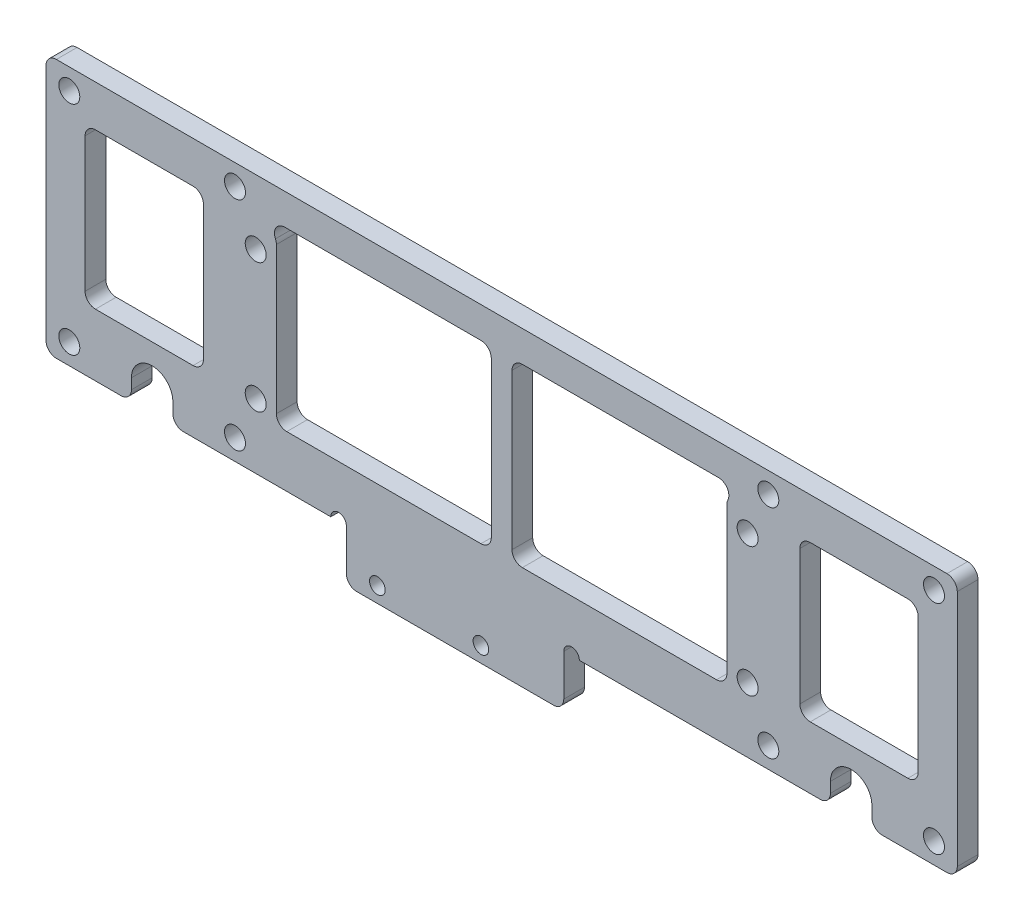
SolidWorks part; units mm, degrees
material "Thornel Mat VMA"
ref_plane "前视基准面" through (0, 0, 0) normal (0, 0, 1) x (1, 0, 0)
ref_plane "上视基准面" through (0, 0, 0) normal (0, 1, 0) x (1, 0, 0)
ref_plane "右视基准面" through (0, 0, 0) normal (1, 0, 0) x (0, 0, -1)
other "Configuration Table"
sketch "草图1" plane through (0, 0, 0) normal (0, 0, 1) x (1, 0, 0)
  line L1 (-88, -25) -> (88, -25)
  line L2 (-88, -25) -> (-88, 25)
  line L3 (-88, 25) -> (88, 25)
  line L4 (88, -25) -> (88, 25)
  line L5 (-88, -25) -> (88, 25) construction
  line L6 (-88, 25) -> (88, -25) construction
  point P0 (0, 0)
  dimension "D1" = 176
  dimension "D2" = 50
extrude "凸台-拉伸1" add sketch "草图1" along normal mid plane 4
sketch "草图2" plane through (0, 0, -2) normal (0, 0, -1) x (-1, 0, 0)
  line L0 (-88, -25) -> (-88, 25) construction
  line L1 (88, -25) -> (-88, -25) construction
  circle A4 centre (51.5, 21) radius 1.65 construction
  circle A5 centre (83.5, 21) radius 1.65 construction
  circle A6 centre (83.5, -21) radius 1.65 construction
  circle A7 centre (51.5, -21) radius 1.65 construction
  circle A8 centre (51.5, 21) radius 2.025
  circle A9 centre (51.5, -21) radius 2.025
  circle A10 centre (83.5, 21) radius 2.025
  circle A11 centre (83.5, -21) radius 2.025
  dimension "D1" = 4.05
  dimension "D2" = 3.3
  dimension "D3" = 139.5
  dimension "D4" = 171.5
  dimension "D5" = 4
  dimension "D6" = 46
extrude "切除-拉伸1" cut sketch "草图2" against normal mid plane 44
mirror "镜向1" about plane through (0, 0, 0) normal (1, 0, 0) of "切除-拉伸1"
sketch "草图3" plane through (0, 0, -2) normal (0, 0, -1) x (-1, 0, 0)
  line L0 (51.5, -21) -> (83.5, -21) construction
  line L1 (88, -25) -> (-88, -25) construction
  line L2 (67.5, -17) -> (64.0359, -19) construction
  line L3 (64.0359, -19) -> (64.0359, -23) construction
  line L4 (64.0359, -23) -> (67.5, -25) construction
  line L5 (67.5, -25) -> (70.9641, -23) construction
  line L6 (70.9641, -23) -> (70.9641, -19) construction
  line L7 (70.9641, -19) -> (67.5, -17) construction
  line L8 (63.5, -21) -> (63.5, -25)
  line L9 (63.5, -25) -> (71.5, -25)
  line L10 (71.5, -25) -> (71.5, -21)
  arc A1 (71.5, -21) -> (63.5, -21) centre (67.5, -21) ccw
extrude "切除-拉伸2" cut sketch "草图3" against normal mid plane 34
mirror "镜向2" about plane through (0, 0, 0) normal (1, 0, 0) of "切除-拉伸2"
fillet "圆角1" radius 2 8 edges at (-63.5, -25, 0) (-71.5, -25, 0) (-88, -25, 0) (-88, 25, 0) (88, 25, 0) (88, -25, 0) (63.5, -25, 0) (71.5, -25, 0)
sketch "草图4" plane through (0, 0, -2) normal (0, 0, -1) x (-1, 0, 0)
  line L0 (0, 0) -> (0, 39.7979) construction
  circle A0 centre (47.5, -12.5) radius 1.65 construction
  circle A1 centre (47.5, 12.5) radius 1.65 construction
  circle A2 centre (47.5, -12.5) radius 1.65 construction
  circle A3 centre (47.5, 12.5) radius 1.65 construction
  circle A4 centre (47.5, -12.5) radius 2.025
  circle A5 centre (47.5, 12.5) radius 2.025
  circle A7 centre (-47.5, 12.5) radius 1.65 construction
  circle A8 centre (-47.5, -12.5) radius 1.65 construction
  circle A9 centre (-47.5, 12.5) radius 2.025
  circle A10 centre (-47.5, -12.5) radius 2.025
  dimension "D1" = 4.05
extrude "切除-拉伸3" cut sketch "草图4" against normal mid plane 10
sketch "草图5" [suppressed] plane through (0, 0, -2) normal (0, 0, -1) x (-1, 0, 0)
  line L0 (61.5, -23) -> (-61.5, -23) construction
  line L1 (-47, -23) -> (47, -23)
  line L2 (-47, -23) -> (-47, -88)
  line L3 (-47, -88) -> (47, -88)
  line L4 (47, -23) -> (47, -88)
  line L5 (0, 0) -> (0, -88) construction
  dimension "D1" = 94
  dimension "D2" = 65
extrude "凸台-拉伸2" [suppressed] add sketch "草图5" against normal up to surface (4 mm away)
sketch "草图7" plane through (0, 0, 2) normal (0, 0, 1) x (1, 0, 0)
  line L5 (-45.0329, 19) -> (-43.5, 15.7427)
  line L6 (-43.5, 15.7427) -> (-43.5, -15.7427)
  line L7 (-43.5, -15.7427) -> (-45.0329, -19)
  line L8 (-45.0329, -19) -> (45.0329, -19)
  line L9 (0, -19) -> (0, 0) construction
  line L10 (-45.0329, 19) -> (45.0329, 19)
  line L11 (0, 0) -> (-43.5, 0) construction
  line L12 (-51.5, 21) -> (-47.5, 12.5) construction
  line L13 (-47.5, 12.5) -> (-47.5, -12.5) construction
  line L14 (-47.5, -12.5) -> (-51.5, -21) construction
  line L15 (-61.5, -25) -> (61.5, -25) construction
  line L16 (45.0329, 19) -> (43.5, 15.7427)
  line L17 (43.5, -15.7427) -> (45.0329, -19)
  line L18 (43.5, 15.7427) -> (43.5, -15.7427)
  line L19 (0, 19) -> (0, -19) construction
  line L20 (-2, 19) -> (-2, -19)
  line L21 (2, 19) -> (2, -19)
  point P23 (0, 19)
  dimension "D1" = 8
  dimension "D2" = 5
  dimension "D3" = 6
  dimension "D4" = 2
  dimension "D5" = 2
extrude "切除-拉伸5" cut sketch "草图7" against normal mid plane 31 contours L20 L10 L5 L6 L7 L8 | L10 L21 L8 L17 L18 L16
sketch "草图8" plane through (0, 0, 2) normal (0, 0, 1) x (1, 0, 0)
  line L0 (-83.5, 21) -> (-51.5, -21) construction
  line L1 (0, 0) -> (0, -25) construction
  line L2 (-80.4524, 17) -> (-57.5952, 17)
  line L3 (-80.4524, 17) -> (-80.4524, -13)
  line L4 (-80.4524, -13) -> (-57.5952, -13)
  line L5 (-57.5952, 17) -> (-57.5952, -13)
  line L6 (-61.5, -25) -> (61.5, -25) construction
  line L7 (80.4524, -13) -> (57.5952, -13)
  line L8 (57.5952, 17) -> (57.5952, -13)
  line L9 (80.4524, 17) -> (57.5952, 17)
  line L10 (80.4524, 17) -> (80.4524, -13)
  circle A0 centre (-51.5, 21) radius 2.025 construction
  arc A1 (-63.5, -21) -> (-71.5, -21) centre (-67.5, -21) ccw construction
  dimension "D1" = 4
  dimension "D2" = 8
extrude "切除-拉伸6" cut sketch "草图8" against normal mid plane 31
fillet "圆角2" radius 2 20 edges at (-45.0329, -19, 0) (-43.5, -15.7427, 0) (-43.5, 15.7427, 0) (-45.0329, 19, 0) (-2, 19, 0) (-2, -19, 0) (43.5, 15.7427, 0) (43.5, -15.7427, 0) (45.0329, -19, 0) (2, -19, 0) (2, 19, 0) (45.0329, 19, 0) (80.4524, -13, 0) (57.5952, -13, 0) (57.5952, 17, 0) (80.4524, 17, 0) (-80.4524, 17, 0) (-57.5952, 17, 0) (-80.4524, -13, 0) (-57.5952, -13, 0)
sketch "草图9" plane through (0, 0, -2) normal (0, 0, -1) x (-1, 0, 0)
  line L0 (0, -52) -> (0, 0) construction
  line L1 (65, -79) -> (-65, -79)
  line L2 (65, -79) -> (65, -25)
  line L3 (65, -25) -> (-65, -25)
  line L4 (-65, -79) -> (-65, -25)
  line L5 (65, -79) -> (-65, -25) construction
  line L6 (65, -25) -> (-65, -79) construction
  line L8 (61.5, -25) -> (-61.5, -25) construction
  point P0 (0, -52)
  dimension "D1" = 54
  dimension "D2" = 130
extrude "凸台-拉伸3" [suppressed] add sketch "草图9" against normal up to surface (4 mm away)
sketch "草图10" [suppressed] plane through (0, 0, -2) normal (0, 0, -1) x (-1, 0, 0)
  line L0 (-65, -79) -> (65, -79) construction
  line L1 (56.25, -26) -> (-56.25, -26)
  line L2 (56.25, -26) -> (56.25, -79)
  line L3 (56.25, -79) -> (-56.25, -79)
  line L4 (-56.25, -26) -> (-56.25, -79)
  line L5 (56.25, -26) -> (-56.25, -79) construction
  line L6 (56.25, -79) -> (-56.25, -26) construction
  line L7 (0, -52.5) -> (0, 0) construction
  point P0 (0, -52.5)
  dimension "D1" = 112.5
  dimension "D2" = 53
extrude "切除-拉伸7" [suppressed] cut sketch "草图10" against normal blind 10
sketch "草图11" plane through (0, 0, 2) normal (0, 0, 1) x (1, 0, 0)
  line L0 (-61.5, -25) -> (61.5, -25) construction
  line L1 (-30, -25) -> (12, -25)
  line L2 (-30, -25) -> (-30, -35)
  line L3 (-30, -35) -> (12, -35)
  line L4 (12, -25) -> (12, -35)
  point P4 (23.2302, -25)
  dimension "D1" = 42
  dimension "D2" = 10
  dimension "D3" = 12
extrude "凸台-拉伸4" add sketch "草图11" against normal up to surface (4 mm away) up to face at (-69.0238, 2, -2)
sketch "草图12" plane through (0, 0, 2) normal (0, 0, 1) x (1, 0, 0)
  line L0 (-30, -35) -> (12, -35) construction
  line L1 (12, -35) -> (12, -25) construction
  line L2 (-4, -32) -> (-24, -32) construction
  circle A1 centre (-4, -32) radius 1.51
  circle A2 centre (-24, -32) radius 1.51
  dimension "D2" = 16
  dimension "D4" = 3.02
  dimension "D1" = 3
  dimension "D3" = 20
extrude "切除-拉伸8" cut sketch "草图12" against normal blind 4
sketch "草图13" plane through (0, 0, 2) normal (0, 0, 1) x (1, 0, 0)
  line L0 (-61.5, -25) -> (-30, -25) construction
  line L1 (12, -25) -> (61.5, -25) construction
  line L2 (-30, -25) -> (-30, -35) construction
  circle A0 centre (-31.5, -25) radius 1.5
  circle A1 centre (13.5, -25) radius 1.5
  dimension "D1" = 3
extrude "切除-拉伸9" cut sketch "草图13" against normal blind 10
sketch "草图14" plane through (0, 0, 2) normal (0, 0, 1) x (1, 0, 0)
  line L0 (-43.5, -15) -> (43.5, -15)
  line L4 (57.5952, 15) -> (57.5952, -11)
  line L5 (78.4524, 17) -> (59.5952, 17)
  line L6 (43.6904, 16.1472) -> (43.6909, 16.1484)
  line L7 (43.5, -15.2956) -> (43.5, 15.2956)
  line L8 (43.6909, -16.1484) -> (43.6904, -16.1472)
  line L9 (4, -19) -> (41.8813, -19)
  line L10 (2, 17) -> (2, -17)
  line L11 (41.8813, 19) -> (4, 19)
  line L12 (43.6904, 16.1472) -> (43.6909, 16.1484)
  line L13 (43.5, -15.2956) -> (43.5, 15.2956)
  line L14 (43.6909, -16.1484) -> (43.6904, -16.1472)
  line L15 (4, -19) -> (41.8813, -19)
  line L16 (2, 17) -> (2, -17)
  line L17 (41.8813, 19) -> (4, 19)
  line L18 (-43.6904, -16.1472) -> (-43.6909, -16.1484)
  line L19 (-43.5, 15.2956) -> (-43.5, -15.2956)
  line L20 (-43.6909, 16.1484) -> (-43.6904, 16.1472)
  line L21 (-4, 19) -> (-41.8813, 19)
  line L22 (-2, -17) -> (-2, 17)
  line L23 (-41.8813, -19) -> (-4, -19)
  line L24 (-43.6904, -16.1472) -> (-43.6909, -16.1484)
  line L25 (-43.5, 15.2956) -> (-43.5, -15.2956)
  line L26 (-43.6909, 16.1484) -> (-43.6904, 16.1472)
  line L27 (-4, 19) -> (-41.8813, 19)
  line L28 (-2, -17) -> (-2, 17)
  line L29 (-41.8813, -19) -> (-4, -19)
  line L30 (80.4524, -11) -> (80.4524, 15)
  line L31 (59.5952, -13) -> (78.4524, -13)
  line L32 (57.5952, 15) -> (57.5952, -11)
  line L33 (78.4524, 17) -> (59.5952, 17)
  line L34 (80.4524, -11) -> (80.4524, 15)
  line L35 (59.5952, -13) -> (78.4524, -13)
  line L36 (-57.5952, -11) -> (-57.5952, 15)
  line L37 (-78.4524, -13) -> (-59.5952, -13)
  line L38 (-80.4524, 15) -> (-80.4524, -11)
  line L39 (-59.5952, 17) -> (-78.4524, 17)
  line L40 (-57.5952, -11) -> (-57.5952, 15)
  line L41 (-78.4524, -13) -> (-59.5952, -13)
  line L42 (-80.4524, 15) -> (-80.4524, -11)
  line L43 (-59.5952, 17) -> (-78.4524, 17)
  circle A1 centre (-51.5, 21) radius 2.025
  circle A2 centre (-51.5, 21) radius 2.025
  circle A3 centre (-83.5, -21) radius 2.025
  circle A4 centre (-83.5, -21) radius 2.025
  circle A5 centre (-83.5, 21) radius 2.025
  circle A6 centre (-83.5, 21) radius 2.025
  circle A7 centre (-51.5, -21) radius 2.025
  circle A8 centre (-51.5, -21) radius 2.025
  circle A9 centre (51.5, 21) radius 2.025
  circle A10 centre (51.5, 21) radius 2.025
  circle A11 centre (83.5, -21) radius 2.025
  circle A12 centre (83.5, -21) radius 2.025
  circle A13 centre (83.5, 21) radius 2.025
  circle A14 centre (83.5, 21) radius 2.025
  circle A15 centre (51.5, -21) radius 2.025
  circle A16 centre (51.5, -21) radius 2.025
  circle A17 centre (-47.5, -12.5) radius 2.025
  circle A18 centre (-47.5, -12.5) radius 2.025
  circle A19 centre (-47.5, 12.5) radius 2.025
  circle A20 centre (-47.5, 12.5) radius 2.025
  circle A21 centre (47.5, 12.5) radius 2.025
  circle A22 centre (47.5, 12.5) radius 2.025
  circle A23 centre (47.5, -12.5) radius 2.025
  circle A24 centre (47.5, -12.5) radius 2.025
  circle A25 centre (-24, -32) radius 1.51
  circle A26 centre (-24, -32) radius 1.51
  circle A27 centre (-4, -32) radius 1.51
  arc A28 (59.5952, 17) -> (57.5952, 15) centre (59.5952, 15) ccw
  arc A29 (80.4524, 15) -> (78.4524, 17) centre (78.4524, 15) ccw
  arc A30 (43.6904, 16.1472) -> (43.5, 15.2956) centre (45.5, 15.2956) ccw
  arc A31 (43.5, -15.2956) -> (43.6904, -16.1472) centre (45.5, -15.2956) ccw
  arc A32 (41.8813, -19) -> (43.6909, -16.1484) centre (41.8813, -17) ccw
  arc A33 (2, -17) -> (4, -19) centre (4, -17) ccw
  arc A34 (4, 19) -> (2, 17) centre (4, 17) ccw
  arc A35 (43.6909, 16.1484) -> (41.8813, 19) centre (41.8813, 17) ccw
  arc A36 (43.6904, 16.1472) -> (43.5, 15.2956) centre (45.5, 15.2956) ccw
  arc A37 (43.5, -15.2956) -> (43.6904, -16.1472) centre (45.5, -15.2956) ccw
  arc A38 (41.8813, -19) -> (43.6909, -16.1484) centre (41.8813, -17) ccw
  arc A39 (2, -17) -> (4, -19) centre (4, -17) ccw
  arc A40 (4, 19) -> (2, 17) centre (4, 17) ccw
  arc A41 (43.6909, 16.1484) -> (41.8813, 19) centre (41.8813, 17) ccw
  arc A42 (-43.6904, -16.1472) -> (-43.5, -15.2956) centre (-45.5, -15.2956) ccw
  arc A43 (-43.5, 15.2956) -> (-43.6904, 16.1472) centre (-45.5, 15.2956) ccw
  arc A44 (-41.8813, 19) -> (-43.6909, 16.1484) centre (-41.8813, 17) ccw
  arc A45 (-2, 17) -> (-4, 19) centre (-4, 17) ccw
  arc A46 (-4, -19) -> (-2, -17) centre (-4, -17) ccw
  arc A47 (-43.6909, -16.1484) -> (-41.8813, -19) centre (-41.8813, -17) ccw
  arc A48 (-43.6904, -16.1472) -> (-43.5, -15.2956) centre (-45.5, -15.2956) ccw
  arc A49 (-43.5, 15.2956) -> (-43.6904, 16.1472) centre (-45.5, 15.2956) ccw
  arc A50 (-41.8813, 19) -> (-43.6909, 16.1484) centre (-41.8813, 17) ccw
  arc A51 (-2, 17) -> (-4, 19) centre (-4, 17) ccw
  arc A52 (-4, -19) -> (-2, -17) centre (-4, -17) ccw
  arc A53 (-43.6909, -16.1484) -> (-41.8813, -19) centre (-41.8813, -17) ccw
  arc A54 (78.4524, -13) -> (80.4524, -11) centre (78.4524, -11) ccw
  arc A55 (57.5952, -11) -> (59.5952, -13) centre (59.5952, -11) ccw
  arc A56 (59.5952, 17) -> (57.5952, 15) centre (59.5952, 15) ccw
  arc A57 (80.4524, 15) -> (78.4524, 17) centre (78.4524, 15) ccw
  arc A58 (78.4524, -13) -> (80.4524, -11) centre (78.4524, -11) ccw
  arc A59 (57.5952, -11) -> (59.5952, -13) centre (59.5952, -11) ccw
  arc A60 (-59.5952, -13) -> (-57.5952, -11) centre (-59.5952, -11) ccw
  arc A61 (-80.4524, -11) -> (-78.4524, -13) centre (-78.4524, -11) ccw
  arc A62 (-78.4524, 17) -> (-80.4524, 15) centre (-78.4524, 15) ccw
  arc A63 (-57.5952, 15) -> (-59.5952, 17) centre (-59.5952, 15) ccw
  arc A64 (-59.5952, -13) -> (-57.5952, -11) centre (-59.5952, -11) ccw
  arc A65 (-80.4524, -11) -> (-78.4524, -13) centre (-78.4524, -11) ccw
  arc A66 (-78.4524, 17) -> (-80.4524, 15) centre (-78.4524, 15) ccw
  arc A67 (-57.5952, 15) -> (-59.5952, 17) centre (-59.5952, 15) ccw
  circle A68 centre (-4, -32) radius 1.51
  dimension "D19" = 4
  dimension "D1" = 0
  dimension "D2" = 0
  dimension "D3" = 0
  dimension "D4" = 0
  dimension "D5" = 0
  dimension "D6" = 0
  dimension "D7" = 0
  dimension "D8" = 0
  dimension "D9" = 0
  dimension "D10" = 0
  dimension "D11" = 0
  dimension "D12" = 0
  dimension "D13" = 0
  dimension "D14" = 0
  dimension "D15" = 0
  dimension "D16" = 0
  dimension "D17" = 0
  dimension "D18" = 0
extrude "凸台-拉伸5" add sketch "草图14" against normal up to surface (4 mm away) contours L24 A53 L29 A52 L28 L0 L25 A48 | L16 A39 L15 A38 L14 A37 L13 L0
fillet "圆角3" radius 2 4 edges at (43.5, -15, 0) (-43.5, -15, 0) (2, -15, 0) (-2, -15, 0)
fillet "圆角4" radius 2 2 edges at (12, -35, 0) (-30, -35, 0)
